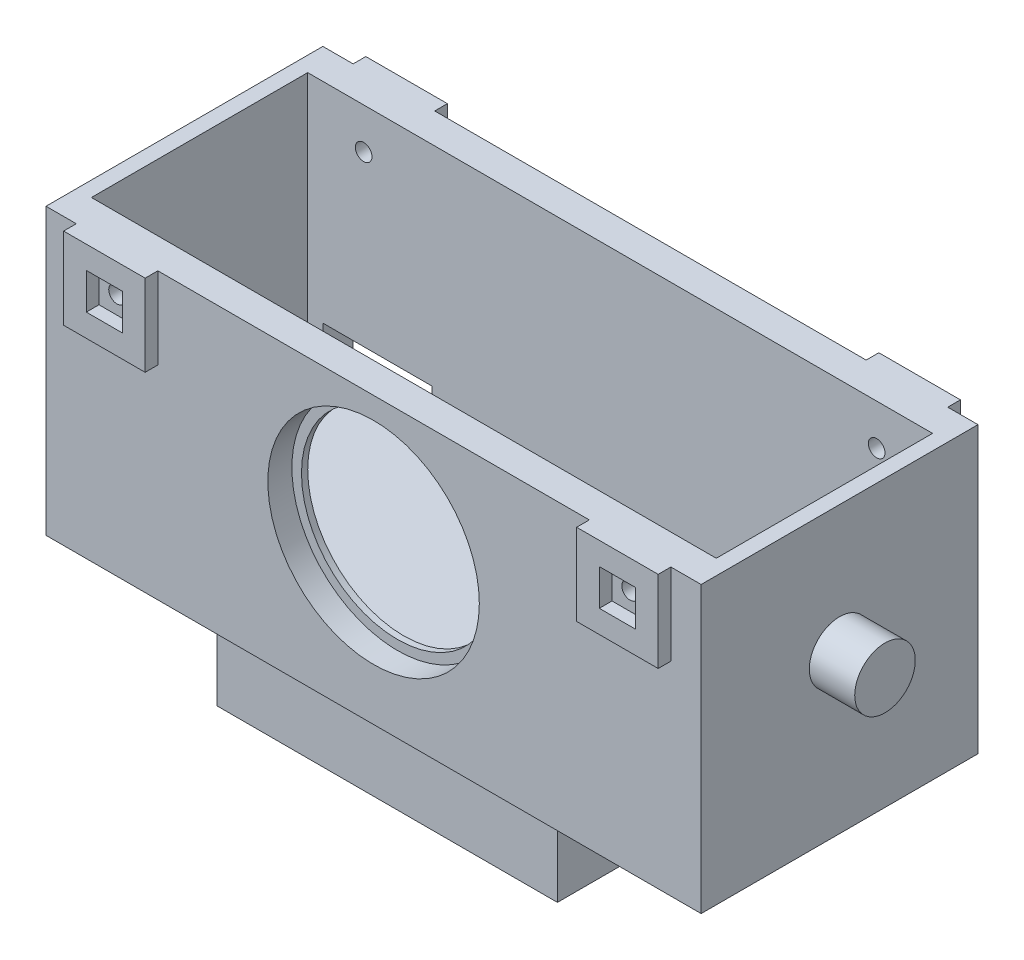
SolidWorks part; units mm, degrees
ref_plane "Front Plane" through (0, 0, 0) normal (0, 0, 1) x (1, 0, 0)
ref_plane "Top Plane" through (0, 0, 0) normal (0, 1, 0) x (1, 0, 0)
ref_plane "Right Plane" through (0, 0, 0) normal (1, 0, 0) x (0, 0, -1)
sketch "Sketch1" plane through (0, 0, 0) normal (1, 0, 0) x (0, 0, -1)
  line L0 (18.2875, 20.8275) -> (-18.2875, 20.8275)
  line L1 (14.2875, -16.8275) -> (-14.2875, -16.8275)
  line L2 (14.2875, -16.8275) -> (14.2875, 16.8275)
  line L3 (14.2875, 16.8275) -> (-14.2875, 16.8275)
  line L4 (-14.2875, -16.8275) -> (-14.2875, 16.8275)
  line L5 (14.2875, -16.8275) -> (-14.2875, 16.8275) construction
  line L6 (14.2875, 16.8275) -> (-14.2875, -16.8275) construction
  line L7 (-18.2875, -20.8275) -> (-18.2875, 20.8275)
  line L8 (18.2875, -20.8275) -> (-18.2875, -20.8275)
  line L9 (18.2875, -20.8275) -> (18.2875, 20.8275)
  point P0 (0, 0)
  dimension "D1" = 28.575
  dimension "D2" = 33.655
  dimension "D3" = 4
extrude "Boss-Extrude1" add sketch "Sketch1" along normal mid plane 82.55
sketch "Sketch2" plane through (-41.275, 0, 0) normal (-1, 0, 0) x (0, 0, 1)
  line L4 (-18.2875, 20.8275) -> (-18.2875, -20.8275)
  line L5 (-18.2875, -20.8275) -> (18.2875, -20.8275)
  line L6 (18.2875, -20.8275) -> (18.2875, 20.8275)
  line L7 (18.2875, 20.8275) -> (-18.2875, 20.8275)
  line L8 (-18.2875, 20.8275) -> (-18.2875, -20.8275)
  line L9 (-18.2875, -20.8275) -> (18.2875, -20.8275)
  line L10 (18.2875, -20.8275) -> (18.2875, 20.8275)
  line L11 (18.2875, 20.8275) -> (-18.2875, 20.8275)
  dimension "D1" = 0
extrude "Boss-Extrude2" add sketch "Sketch2" along normal blind 2
mirror "Mirror1" about plane through (0, 0, 0) normal (1, 0, 0) of "Boss-Extrude2"
sketch "Sketch3" plane through (0, 20.8275, 0) normal (0, 1, 0) x (1, 0, 0)
  line L4 (43.275, 18.2875) -> (-43.275, 18.2875)
  line L5 (-43.275, 18.2875) -> (-43.275, -18.2875)
  line L6 (-43.275, -18.2875) -> (43.275, -18.2875)
  line L7 (43.275, -18.2875) -> (43.275, 18.2875)
  line L8 (43.275, 18.2875) -> (-43.275, 18.2875)
  line L9 (-43.275, 18.2875) -> (-43.275, -18.2875)
  line L10 (-43.275, -18.2875) -> (43.275, -18.2875)
  line L11 (43.275, -18.2875) -> (43.275, 18.2875)
  dimension "D1" = 0
extrude "Cut-Extrude1" cut sketch "Sketch3" against normal blind 4
sketch "Sketch4" plane through (0, 0, -18.2875) normal (0, 0, -1) x (-1, 0, 0)
  line L0 (-43.275, 16.8275) -> (43.275, 16.8275) construction
  line L1 (-28.4998, 6.0523) -> (-39.275, 6.0523)
  line L2 (-28.4998, 6.0523) -> (-28.4998, 16.8275)
  line L3 (-28.4998, 16.8275) -> (-39.275, 16.8275)
  line L4 (-39.275, 6.0523) -> (-39.275, 16.8275)
  line L5 (-28.4998, 6.0523) -> (-39.275, 16.8275) construction
  line L6 (-28.4998, 16.8275) -> (-39.275, 6.0523) construction
  line L7 (-43.275, 16.8275) -> (-43.275, -20.8275) construction
  line L8 (-31.4998, 9.0523) -> (-36.275, 9.0523)
  line L9 (-31.4998, 9.0523) -> (-31.4998, 13.8275)
  line L10 (-31.4998, 13.8275) -> (-36.275, 13.8275)
  line L11 (-36.275, 9.0523) -> (-36.275, 13.8275)
  line L12 (-31.4998, 9.0523) -> (-36.275, 13.8275) construction
  line L13 (-31.4998, 13.8275) -> (-36.275, 9.0523) construction
  point P0 (-33.8874, 11.4399)
  point P7 (-33.8874, 11.4399)
  dimension "D1" = 3
  dimension "D2" = 4.7752
  dimension "D3" = 4
extrude "Boss-Extrude3" add sketch "Sketch4" along normal blind 1.6764
mirror "Mirror2" about plane through (0, 0, 0) normal (1, 0, 0) of "Boss-Extrude3"
mirror "Mirror3" about plane through (0, 0, 0) normal (0, 0, 1) of "Boss-Extrude3", "Mirror2"
sketch "Sketch5" plane through (0, 0, 18.2875) normal (0, 0, 1) x (1, 0, 0)
  line L0 (-33.8874, 13.8275) -> (-33.8874, 9.0523) construction
  line L1 (-31.4998, 13.8275) -> (-36.275, 13.8275) construction
  line L2 (-36.275, 9.0523) -> (-31.4998, 9.0523) construction
  circle A0 centre (-33.8874, 11.4399) radius 1.1
  dimension "D1" = 2.2
extrude "Cut-Extrude2" cut sketch "Sketch5" against normal through all
mirror "Mirror4" about plane through (0, 0, 0) normal (1, 0, 0) of "Cut-Extrude2"
sketch "Sketch6" plane through (-43.275, 0, 0) normal (-1, 0, 0) x (0, 0, 1)
  line L0 (0, 16.8275) -> (0, -20.8275) construction
  line L1 (-18.2875, 16.8275) -> (18.2875, 16.8275) construction
  line L2 (-18.2875, -20.8275) -> (18.2875, -20.8275) construction
  circle A0 centre (0, 0) radius 4
  dimension "D1" = 8
extrude "Boss-Extrude4" add sketch "Sketch6" along normal blind 6
mirror "Mirror5" about plane through (0, 0, 0) normal (1, 0, 0) of "Boss-Extrude4"
sketch "Sketch7" plane through (0, 0, 18.2875) normal (0, 0, 1) x (1, 0, 0)
  circle A0 centre (0, 0) radius 12.7
  dimension "D1" = 25.4
extrude "Cut-Extrude3" cut sketch "Sketch7" against normal up to surface (4 mm away) up to face at (0, 0, 14.2875)
sketch "Sketch8" plane through (0, 0, 18.2875) normal (0, 0, 1) x (1, 0, 0)
  circle A0 centre (0, 0) radius 13.97
  dimension "D1" = 27.94
extrude "Cut-Extrude4" cut sketch "Sketch8" against normal blind 3.175
sketch "Sketch9" plane through (0, 0, -18.2875) normal (0, 0, -1) x (-1, 0, 0)
  line L0 (39.275, 16.8275) -> (39.275, 6.0523) construction
  line L1 (24.875, -10.8275) -> (39.275, -10.8275)
  line L2 (24.875, -10.8275) -> (24.875, -16.8275)
  line L3 (24.875, -16.8275) -> (39.275, -16.8275)
  line L4 (39.275, -10.8275) -> (39.275, -16.8275)
  line L5 (24.875, -10.8275) -> (39.275, -16.8275) construction
  line L6 (24.875, -16.8275) -> (39.275, -10.8275) construction
  line L7 (-43.275, -20.8275) -> (43.275, -20.8275) construction
  point P0 (32.075, -13.8275)
  dimension "D1" = 14.4
  dimension "D2" = 4
  dimension "D3" = 6
extrude "Cut-Extrude5" cut sketch "Sketch9" against normal blind 4
sketch "Sketch10" plane through (0, -20.8275, 0) normal (0, -1, 0) x (1, 0, 0)
  line L1 (18.5, -12.5) -> (-18.5, -12.5)
  line L2 (18.5, -12.5) -> (18.5, 12.5)
  line L3 (18.5, 12.5) -> (-18.5, 12.5)
  line L4 (-18.5, -12.5) -> (-18.5, 12.5)
  line L5 (18.5, -12.5) -> (-18.5, 12.5) construction
  line L6 (18.5, 12.5) -> (-18.5, -12.5) construction
  line L7 (22.5, -16.5) -> (-22.5, -16.5)
  line L8 (22.5, -16.5) -> (22.5, 16.5)
  line L9 (22.5, 16.5) -> (-22.5, 16.5)
  line L10 (-22.5, -16.5) -> (-22.5, 16.5)
  line L11 (22.5, -16.5) -> (-22.5, 16.5) construction
  line L12 (22.5, 16.5) -> (-22.5, -16.5) construction
  point P0 (0, 0)
  point P6 (0, 0)
  dimension "D1" = 37
  dimension "D2" = 25
  dimension "D3" = 4
  dimension "D4" = 4
extrude "Boss-Extrude5" add sketch "Sketch10" along normal blind 10
sketch "Sketch11" plane through (0, -30.8275, 0) normal (0, -1, 0) x (1, 0, 0)
  line L1 (19.5, -13.5) -> (-19.5, -13.5)
  line L2 (19.5, -13.5) -> (19.5, 13.5)
  line L3 (19.5, 13.5) -> (-19.5, 13.5)
  line L4 (-22.5, 16.5) -> (-22.5, -16.5)
  line L5 (-22.5, -16.5) -> (22.5, -16.5)
  line L6 (22.5, -16.5) -> (22.5, 16.5)
  line L7 (22.5, 16.5) -> (-22.5, 16.5)
  line L8 (-22.5, 16.5) -> (-22.5, -16.5) construction
  line L9 (-22.5, -16.5) -> (22.5, -16.5) construction
  line L10 (22.5, -16.5) -> (22.5, 16.5) construction
  line L11 (22.5, 16.5) -> (-22.5, 16.5) construction
  line L12 (-19.5, -13.5) -> (-19.5, 13.5)
  line L13 (19.5, -13.5) -> (-19.5, 13.5) construction
  line L14 (19.5, 13.5) -> (-19.5, -13.5) construction
  point P2 (0, 0)
  dimension "D2" = 3
  dimension "D3" = 3
  dimension "D1" = 0
extrude "Cut-Extrude7" cut sketch "Sketch11" against normal blind 3.175
sketch "Sketch14" plane through (22.5, 0, 0) normal (1, 0, 0) x (0, 0, -1)
  line L0 (16.5, -20.8275) -> (-16.5, -20.8275) construction
  line L1 (8, -26.8275) -> (-8, -26.8275)
  line L2 (8, -26.8275) -> (8, -20.8275)
  line L3 (8, -20.8275) -> (-8, -20.8275)
  line L4 (-8, -26.8275) -> (-8, -20.8275)
  line L5 (8, -26.8275) -> (-8, -20.8275) construction
  line L6 (8, -20.8275) -> (-8, -26.8275) construction
  line L7 (0, -20.8275) -> (0, -30.8275) construction
  line L8 (16.5, -30.8275) -> (-16.5, -30.8275) construction
  point P0 (0, -23.8275)
  dimension "D1" = 6
  dimension "D2" = 16
extrude "Cut-Extrude8" cut sketch "Sketch14" against normal blind 4
